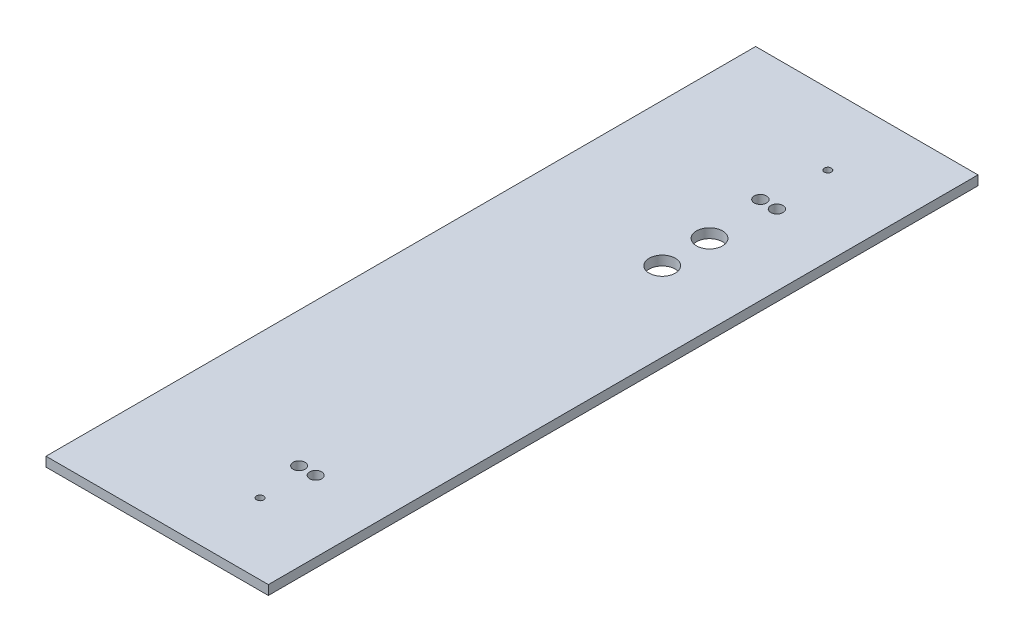
SolidWorks part; units mm, degrees
ref_plane "Front Plane" through (0, 0, 0) normal (0, 0, 1) x (1, 0, 0)
ref_plane "Top Plane" through (0, 0, 0) normal (0, 1, 0) x (1, 0, 0)
ref_plane "Right Plane" through (0, 0, 0) normal (1, 0, 0) x (0, 0, -1)
sketch "Sketch1" plane through (0, 0, 0) normal (0, 1, 0) x (1, 0, 0)
  line L1 (0, 0) -> (188, 0)
  line L2 (0, 0) -> (0, 600)
  line L3 (0, 600) -> (188, 600)
  line L4 (188, 0) -> (188, 600)
extrude "Boss-Extrude1" add sketch "Sketch1" along normal blind 8
sketch "Sketch2" plane through (0, 8, 0) normal (0, 1, 0) x (1, 0, 0)
  line L0 (188, 0) -> (188, 600) construction
  line L1 (0, 0) -> (188, 0) construction
  line L2 (188, 600) -> (0, 600) construction
  circle A0 centre (114, 100) radius 5.1
  circle A1 centre (128, 100) radius 5.1
  circle A2 centre (121, 60) radius 3
  circle A3 centre (121, 440) radius 11
  circle A4 centre (121, 400) radius 11
  circle A5 centre (114, 490) radius 5.2
  circle A6 centre (128, 490) radius 5.2
  circle A7 centre (121, 540) radius 3
  dimension "D1" = 10.2
  dimension "D2" = 10.2
  dimension "D4" = 60
  dimension "D9" = 22
  dimension "D10" = 22
  dimension "D11" = 10.4
  dimension "D12" = 10.4
  dimension "D13" = 6
  dimension "D19" = 6
  dimension "D24" = 67
  dimension "D3" = 14
  dimension "D5" = 100
  dimension "D6" = 100
  dimension "D7" = 67
  dimension "D8" = 60
  dimension "D14" = 67
  dimension "D15" = 67
  dimension "D16" = 60
  dimension "D17" = 14
  dimension "D18" = 60
  dimension "D20" = 110
  dimension "D21" = 110
  dimension "D22" = 160
  dimension "D23" = 200
extrude "Cut-Extrude1" cut sketch "Sketch2" against normal through all
